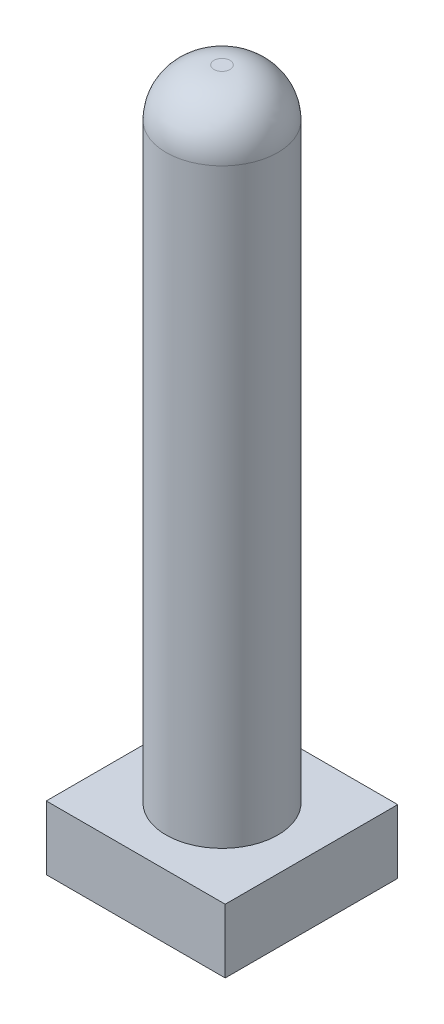
SolidWorks part; units mm, degrees
ref_plane "Front Plane" through (0, 0, 0) normal (0, 0, 1) x (1, 0, 0)
ref_plane "Top Plane" through (0, 0, 0) normal (0, 1, 0) x (1, 0, 0)
ref_plane "Right Plane" through (0, 0, 0) normal (1, 0, 0) x (0, 0, -1)
sketch "Sketch1" plane through (0, 0, 0) normal (0, 1, 0) x (1, 0, 0)
  line L1 (-2.8, -2.7) -> (2.8, -2.7)
  line L2 (-2.8, -2.7) -> (-2.8, 2.7)
  line L3 (-2.8, 2.7) -> (2.8, 2.7)
  line L4 (2.8, -2.7) -> (2.8, 2.7)
  line L5 (-2.8, -2.7) -> (2.8, 2.7) construction
  line L6 (-2.8, 2.7) -> (2.8, -2.7) construction
  point P0 (0, 0)
  dimension "D1" = 5.6
  dimension "D2" = 5.4
extrude "Boss-Extrude1" add sketch "Sketch1" along normal blind 2
sketch "Sketch2" plane through (0, 2, 0) normal (0, 1, 0) x (1, 0, 0)
  circle A0 centre (0, 0) radius 1.75
  dimension "D1" = 3.5
sketch "Sketch3" plane through (0, 0, 0) normal (0, -1, 0) x (1, 0, 0)
  circle A0 centre (0, 0) radius 1.2
  circle A1 centre (0, 0) radius 0.95
  point P0 (0, 0)
  dimension "D1" = 2.4
  dimension "D2" = 1.9
extrude "Cut-Extrude2" cut sketch "Sketch3" against normal blind 9.5 contours A1
sketch "Sketch7" plane through (0, 0, 0) normal (0, -1, 0) x (1, 0, 0)
  circle A0 centre (0, 0) radius 1.2
  dimension "D1" = 2.4
extrude "Cut-Extrude4" cut sketch "Sketch7" against normal blind 2.8
extrude "Boss-Extrude2" add sketch "Sketch2" along normal blind 20
fillet "Fillet2" radius 1.5 1 edges at (0, 22, 1.75)
sketch "Sketch8" plane through (0, 0, 0) normal (0, -1, 0) x (1, 0, 0)
  circle A0 centre (0, 0) radius 0.95
  dimension "D1" = 1.9
extrude "Cut-Extrude5" cut sketch "Sketch8" against normal blind 9.5
